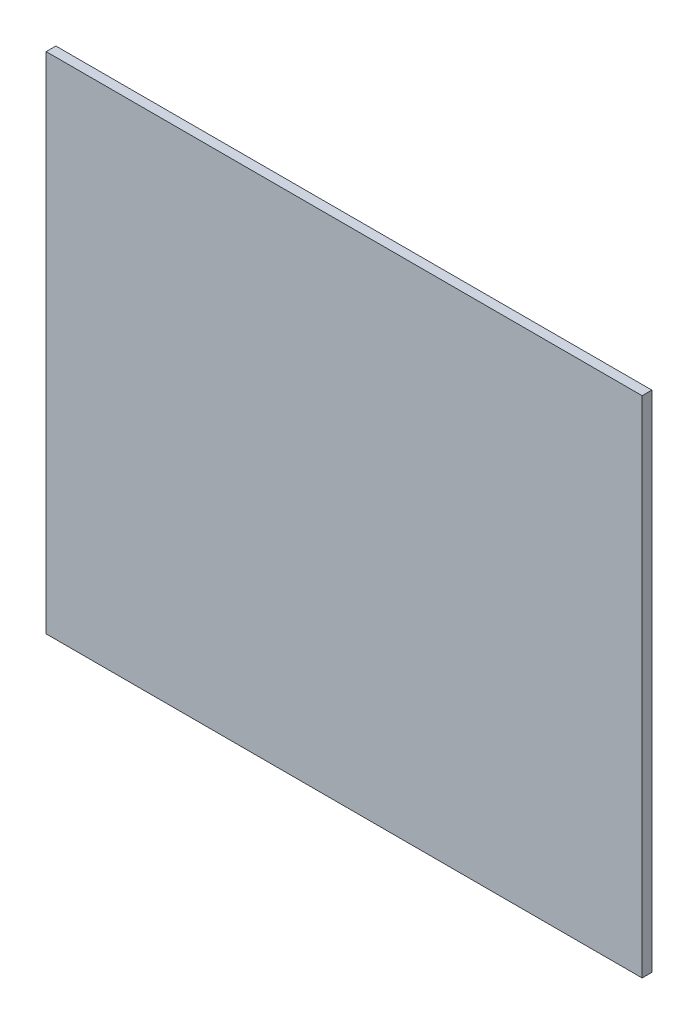
SolidWorks part; units mm, degrees
ref_plane "Front Plane" through (0, 0, 0) normal (0, 0, 1) x (1, 0, 0)
ref_plane "Top Plane" through (0, 0, 0) normal (0, 1, 0) x (1, 0, 0)
ref_plane "Right Plane" through (0, 0, 0) normal (1, 0, 0) x (0, 0, -1)
sketch "Sketch1" plane through (0, 0, 0) normal (0, 0, 1) x (1, 0, 0)
  line L1 (0, 0) -> (390, 0)
  line L2 (0, 0) -> (0, 330)
  line L3 (0, 330) -> (390, 330)
  line L4 (390, 0) -> (390, 330)
  dimension "D1" = 330
  dimension "D2" = 390
extrude "Boss-Extrude1" add sketch "Sketch1" along normal blind 6.35
